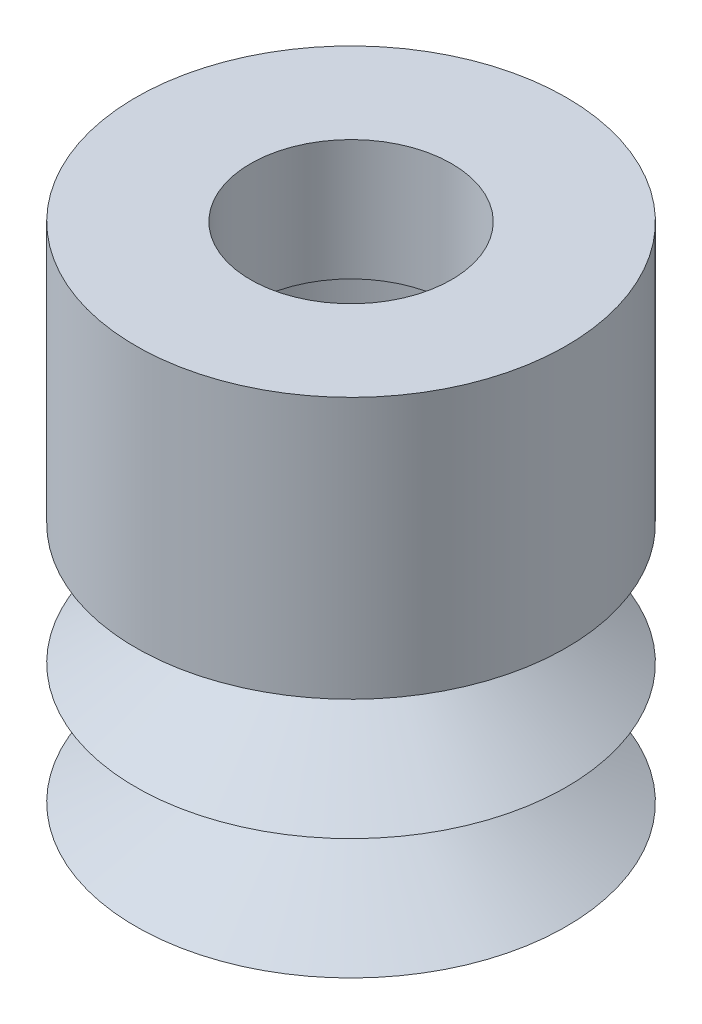
SolidWorks part; units mm, degrees
ref_plane "Plan de face" through (0, 0, 0) normal (0, 0, 1) x (1, 0, 0)
ref_plane "Plan de dessus" through (0, 0, 0) normal (0, 1, 0) x (1, 0, 0)
ref_plane "Plan de droite" through (0, 0, 0) normal (1, 0, 0) x (0, 0, -1)
sketch "Esquisse1" plane through (0, 0, 0) normal (0, 0, 1) x (1, 0, 0)
  line L0 (0, 0) -> (0, 12.5) construction
  line L2 (-2.5, 12.5) -> (-5.35, 12.5)
  line L3 (-5.35, 12.5) -> (-5.35, 6)
  line L4 (-5.35, 6) -> (-2.65, 4.847)
  line L5 (-2.65, 4.847) -> (-5.35, 3)
  line L6 (-5.35, 3) -> (-2.65, 1.4877)
  line L7 (-2.65, 1.4877) -> (-5.35, 0)
  line L8 (-5.35, 0) -> (-3.1518, 0)
  line L9 (-3.1518, 0) -> (-1.05, 1.4877)
  line L10 (-1.05, 1.4877) -> (-3.75, 3)
  line L11 (-3.75, 3) -> (-2, 4.1971)
  line L15 (-5.35, 6) -> (-5.35, 0) construction
  line L16 (-2.65, 4.847) -> (-2.65, 1.4877) construction
  line L17 (-2, 4.1971) -> (-2, 7.9)
  line L18 (-2, 7.9) -> (-4, 7.9)
  line L19 (-4, 7.9) -> (-4, 9.5)
  line L20 (-4, 9.5) -> (-2.5, 9.5)
  line L21 (-2.5, 9.5) -> (-2.5, 12.5)
  line L22 (-2.5, 12.5) -> (0, 12.5) construction
  line L23 (0, 0) -> (-3.1518, 0) construction
  line L24 (-3.75, 3) -> (-5.35, 3) construction
  line L25 (-1.05, 1.4877) -> (-2.65, 1.4877) construction
  dimension "D1" = 5.35
  dimension "D2" = 12.5
  dimension "D3" = 3
  dimension "D4" = 4
  dimension "D5" = 1.6
  dimension "D6" = 3
  dimension "D7" = 2.7
  dimension "D8" = 2
  dimension "D9" = 2.5
revolve "Révolution1" add sketch "Esquisse1" angle 360 about L0
